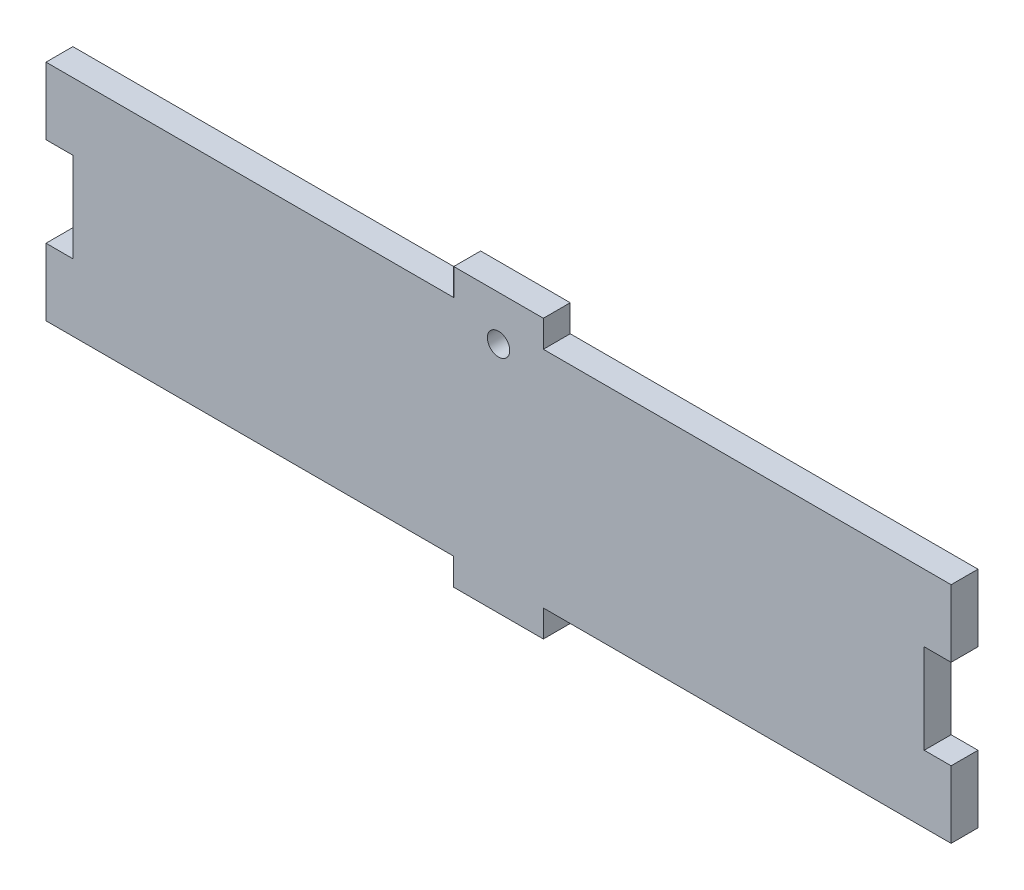
SolidWorks part; units mm, degrees
ref_plane "Plan de face" through (0, 0, 0) normal (0, 0, 1) x (1, 0, 0)
ref_plane "Plan de dessus" through (0, 0, 0) normal (0, 1, 0) x (1, 0, 0)
ref_plane "Plan de droite" through (0, 0, 0) normal (1, 0, 0) x (0, 0, -1)
sketch "Esquisse6" plane through (0, 0, 0) normal (0, 0, 1) x (1, 0, 0)
  line L0 (-98.9969, 22.2958) -> (-7.9969, 22.2958) construction
  line L2 (12.0031, 22.2958) -> (-7.9969, 22.2958) construction
  line L3 (97.0031, 7.2958) -> (97.0031, 28.2958) construction
  line L4 (97.0031, 7.2958) -> (97.0031, -12.7042) construction
  line L5 (97.0031, -33.7042) -> (97.0031, -12.7042) construction
  line L7 (12.0031, -27.7042) -> (-7.9969, -27.7042) construction
  line L8 (-7.9969, -27.7042) -> (-98.9969, -27.7042) construction
  line L9 (-92.9969, -12.7042) -> (-92.9969, -33.7042) construction
  line L10 (-92.9969, 7.2958) -> (-92.9969, -12.7042) construction
  line L11 (-92.9969, 28.2958) -> (-92.9969, 7.2958) construction
  line L12 (12.0031, 22.2958) -> (103.0031, 22.2958) construction
  line L13 (12.0031, 22.2958) -> (97.0031, 22.2958)
  line L14 (12.0031, 22.2958) -> (-7.9969, 22.2958)
  line L15 (97.0031, 7.2958) -> (97.0031, 22.2958)
  line L16 (97.0031, 7.2958) -> (97.0031, -12.7042)
  line L17 (97.0031, -27.7042) -> (97.0031, -12.7042)
  line L18 (103.0031, -27.7042) -> (12.0031, -27.7042) construction
  line L19 (12.0031, -27.7042) -> (-7.9969, -27.7042)
  line L20 (97.0031, -27.7042) -> (12.0031, -27.7042)
  line L21 (-92.9969, -12.7042) -> (-92.9969, -27.7042)
  line L22 (-92.9969, 7.2958) -> (-92.9969, -12.7042)
  line L23 (-92.9969, 22.2958) -> (-92.9969, 7.2958)
  line L55 (-92.9969, 22.2958) -> (-7.9969, 22.2958)
  line L67 (-7.9969, -27.7042) -> (-92.9969, -27.7042)
extrude "Boss.-Extru.2" add sketch "Esquisse6" against normal blind 6
sketch "Esquisse7" plane through (0, 0, 0) normal (0, 0, 1) x (1, 0, 0)
  line L0 (97.0031, 7.2958) -> (103.0031, 7.2958) construction
  line L1 (103.0031, 7.2958) -> (103.0031, 28.2958) construction
  line L3 (97.0031, 28.2958) -> (97.0031, 7.2958) construction
  line L4 (12.0031, 28.2958) -> (-7.9969, 28.2958)
  line L5 (-7.9969, 28.2958) -> (-7.9969, 22.2958)
  line L6 (-7.9969, 22.2958) -> (12.0031, 22.2958)
  line L7 (12.0031, 22.2958) -> (12.0031, 28.2958)
  line L8 (12.0031, 28.2958) -> (-7.9969, 28.2958)
  line L9 (-7.9969, 28.2958) -> (-7.9969, 22.2958)
  line L10 (-7.9969, 22.2958) -> (12.0031, 22.2958)
  line L11 (12.0031, 22.2958) -> (12.0031, 28.2958)
  line L12 (103.0031, -33.7042) -> (103.0031, -12.7042) construction
  line L13 (103.0031, -12.7042) -> (97.0031, -12.7042) construction
  line L14 (97.0031, -12.7042) -> (97.0031, -33.7042) construction
  line L16 (97.0031, 7.2958) -> (103.0031, 7.2958)
  line L17 (103.0031, 7.2958) -> (103.0031, 22.2958)
  line L19 (97.0031, 22.2958) -> (97.0031, 7.2958)
  line L20 (103.0031, -27.7042) -> (103.0031, -12.7042)
  line L21 (103.0031, -12.7042) -> (97.0031, -12.7042)
  line L22 (97.0031, -12.7042) -> (97.0031, -27.7042)
  line L24 (-92.9969, -33.7042) -> (-92.9969, -12.7042) construction
  line L25 (-92.9969, -12.7042) -> (-98.9969, -12.7042) construction
  line L26 (-98.9969, -12.7042) -> (-98.9969, -33.7042) construction
  line L28 (12.0031, -27.7042) -> (-7.9969, -27.7042)
  line L29 (-7.9969, -27.7042) -> (-7.9969, -33.7042)
  line L30 (-7.9969, -33.7042) -> (12.0031, -33.7042)
  line L31 (12.0031, -33.7042) -> (12.0031, -27.7042)
  line L32 (12.0031, -27.7042) -> (-7.9969, -27.7042)
  line L33 (-7.9969, -27.7042) -> (-7.9969, -33.7042)
  line L34 (-7.9969, -33.7042) -> (12.0031, -33.7042)
  line L35 (12.0031, -33.7042) -> (12.0031, -27.7042)
  line L36 (-98.9969, 7.2958) -> (-92.9969, 7.2958) construction
  line L37 (-92.9969, 7.2958) -> (-92.9969, 28.2958) construction
  line L39 (-98.9969, 28.2958) -> (-98.9969, 7.2958) construction
  line L40 (-92.9969, -27.7042) -> (-92.9969, -12.7042)
  line L41 (-92.9969, -12.7042) -> (-98.9969, -12.7042)
  line L42 (-98.9969, -12.7042) -> (-98.9969, -27.7042)
  line L44 (-98.9969, 7.2958) -> (-92.9969, 7.2958)
  line L45 (-92.9969, 7.2958) -> (-92.9969, 22.2958)
  line L47 (-98.9969, 22.2958) -> (-98.9969, 7.2958)
  line L204 (-7.9969, -27.7042) -> (-98.9969, -27.7042) construction
  line L205 (-92.9969, -27.7042) -> (-98.9969, -27.7042)
  line L206 (103.0031, -27.7042) -> (12.0031, -27.7042) construction
  line L207 (103.0031, -27.7042) -> (97.0031, -27.7042)
  line L208 (12.0031, 22.2958) -> (103.0031, 22.2958) construction
  line L209 (97.0031, 22.2958) -> (103.0031, 22.2958)
  line L210 (-98.9969, 22.2958) -> (-7.9969, 22.2958) construction
  line L211 (-98.9969, 22.2958) -> (-92.9969, 22.2958)
  dimension "D1" = 0
  dimension "D2" = 0
extrude "Boss.-Extru.3" add sketch "Esquisse7" against normal blind 6
sketch "Esquisse8" plane through (0, 0, 0) normal (0, 0, 1) x (1, 0, 0)
  line L0 (0, 0) -> (0, 52.1151) construction
  line L1 (0, 0) -> (109.0976, 0) construction
  line L2 (2.0031, 28.2958) -> (2.0031, -4.6566) construction
  line L3 (12.0031, 28.2958) -> (-7.9969, 28.2958) construction
  line L4 (-7.9969, 22.2958) -> (12.0031, 22.2958) construction
  line L5 (-7.9969, 28.2958) -> (-7.9969, 22.2958) construction
  line L6 (-7.9969, 22.2958) -> (-98.9969, 22.2958) construction
  line L7 (12.0031, 22.2958) -> (12.0031, 28.2958) construction
  line L8 (103.0031, 22.2958) -> (12.0031, 22.2958) construction
  circle A0 centre (2.0031, 18.2958) radius 2.5
  dimension "D1" = 5
  dimension "D2" = 4
extrude "Enlèv. mat.-Extru.2" cut sketch "Esquisse8" against normal blind 6
